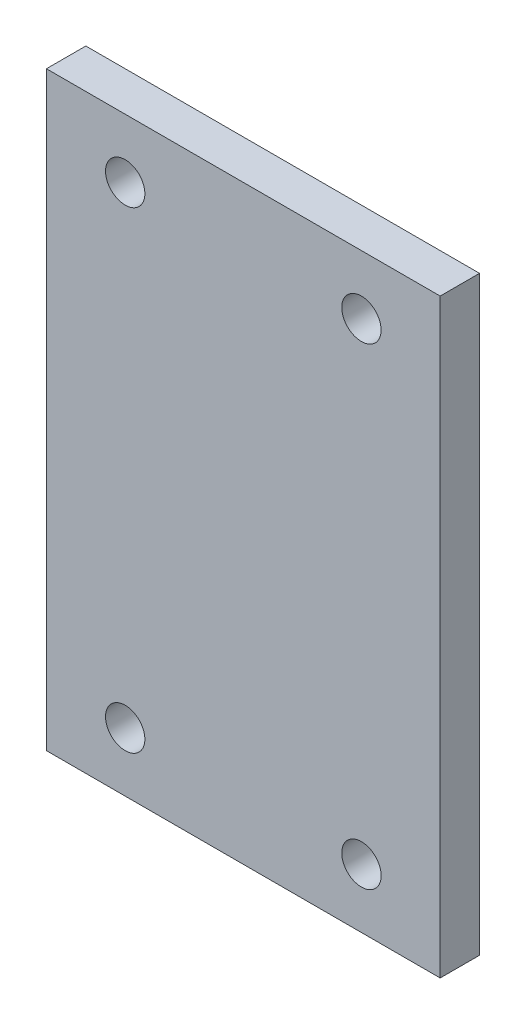
SolidWorks part; units mm, degrees
ref_plane "Front Plane" through (0, 0, 0) normal (0, 0, 1) x (1, 0, 0)
ref_plane "Top Plane" through (0, 0, 0) normal (0, 1, 0) x (1, 0, 0)
ref_plane "Right Plane" through (0, 0, 0) normal (1, 0, 0) x (0, 0, -1)
sketch "Sketch1" plane through (0, 0, 0) normal (0, 0, 1) x (1, 0, 0)
  line L0 (-23.2441, 112.6834) -> (-23.2441, -6.0422) construction
  line L1 (-48.6441, 94.1422) -> (2.1559, 94.1422)
  line L2 (-48.6441, 94.1422) -> (-48.6441, 17.9422)
  line L3 (-48.6441, 17.9422) -> (2.1559, 17.9422)
  line L4 (2.1559, 94.1422) -> (2.1559, 17.9422)
  line L5 (-48.6441, 94.1422) -> (2.1559, 17.9422) construction
  line L6 (-48.6441, 17.9422) -> (2.1559, 94.1422) construction
  line L7 (-76.398, 56.0422) -> (42.8501, 56.0422) construction
  line L8 (29.9098, 56.0422) -> (-89.3383, 56.0422) construction
  circle A0 centre (-38.4841, 25.5622) radius 2.54
  circle A1 centre (-8.0041, 25.5622) radius 2.54
  circle A2 centre (-8.0041, 86.5222) radius 2.54
  circle A3 centre (-38.4841, 86.5222) radius 2.54
  point P0 (-23.2441, 56.0422)
  point P19 (0, 0)
  point P20 (0, 0)
  dimension "D1" = 7.62
  dimension "D2" = 10.16
  dimension "D3" = 50.8
  dimension "D4" = 76.2
extrude "Boss-Extrude1" add sketch "Sketch1" along normal blind 5.08
sketch "Sketch2" plane through (0, 17.9422, 0) normal (0, -1, 0) x (1, 0, 0)
  line L1 (-48.6441, 5.08) -> (-48.6441, 0) construction
  line L2 (-23.2441, 6.3566) -> (-23.2441, -4.067) construction
  circle A0 centre (-38.4382, 2.54) radius 2.1
  circle A1 centre (-8.0501, 2.54) radius 2.1
  point P4 (-48.6441, 2.54)
extrude "Cut-Extrude1" cut sketch "Sketch2" against normal blind 4
